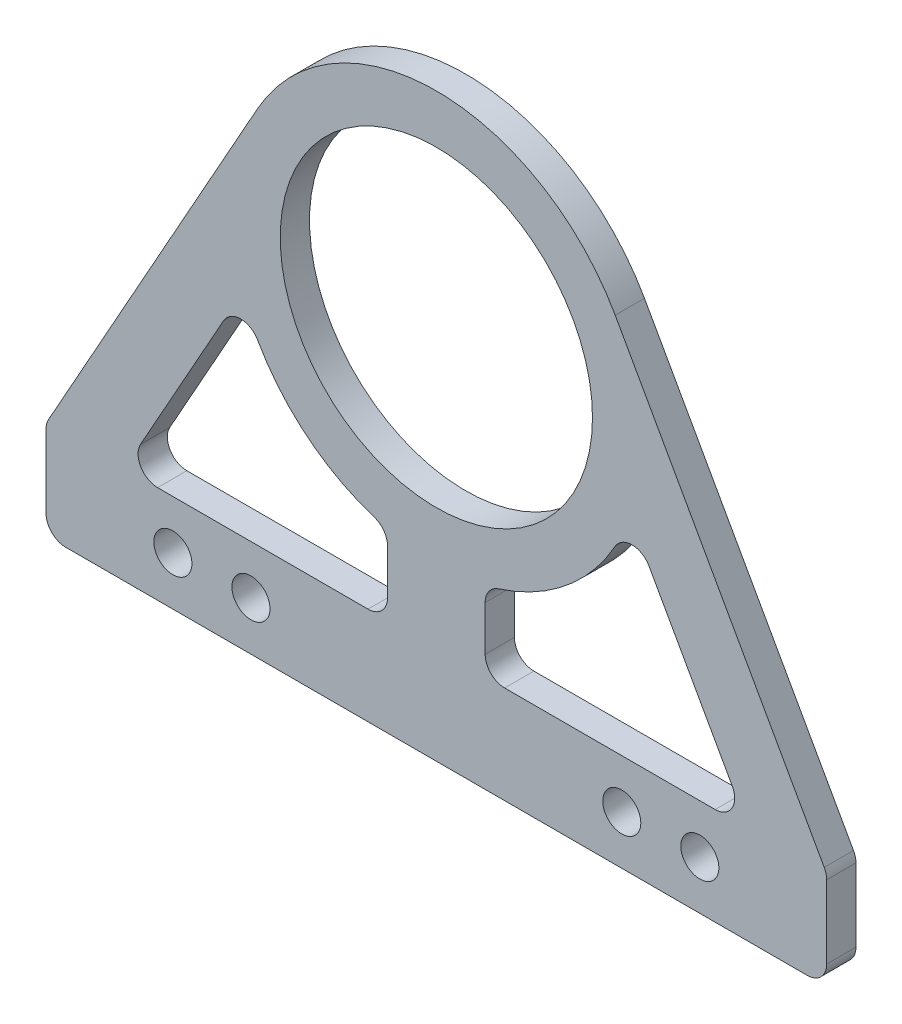
SolidWorks part; units mm, degrees
material "Thornel Mat VMA"
ref_plane "前视基准面" through (0, 0, 0) normal (0, 0, 1) x (1, 0, 0)
ref_plane "上视基准面" through (0, 0, 0) normal (0, 1, 0) x (1, 0, 0)
ref_plane "右视基准面" through (0, 0, 0) normal (1, 0, 0) x (0, 0, -1)
other "Configuration Table"
sketch "草图1" plane through (0, 0, 0) normal (0, 0, 1) x (1, 0, 0)
  line L0 (-40, -28.5) -> (-40, -38.5)
  line L1 (40, -28.5) -> (18.3284, 10.2504)
  line L2 (-18.3284, 10.2504) -> (-40, -28.5)
  line L3 (-40, -38.5) -> (40, -38.5)
  line L4 (40, -38.5) -> (40, -28.5)
  line L5 (-40, -33.5) -> (40, -33.5) construction
  circle A0 centre (0, 0) radius 16
  arc A1 (18.3284, 10.2504) -> (-18.3284, 10.2504) centre (0, 0) ccw
  circle A2 centre (27, -33.5) radius 1.95
  circle A3 centre (19, -33.5) radius 1.95
  circle A4 centre (-27, -33.5) radius 1.95
  circle A5 centre (-19, -33.5) radius 1.95
  dimension "D1" = 32
  dimension "D2" = 5
  dimension "D6" = 3.9
  dimension "D7" = 8
  dimension "D8" = 13
  dimension "D9" = 8
  dimension "D10" = 13
  dimension "D3" = 10
  dimension "D4" = 80
  dimension "D5" = 38.5
extrude "凸台-拉伸1" add sketch "草图1" along normal blind 3
sketch "草图2" plane through (0, 0, 3) normal (0, 0, 1) x (1, 0, 0)
  line L0 (-31.9797, -28.5) -> (-5, -28.5)
  line L1 (-5, -20.3961) -> (-5, -28.5)
  line L2 (0, 0) -> (0, -28.5) construction
  line L3 (-19.8591, -6.8276) -> (-31.9797, -28.5)
  line L4 (-18.3284, 10.2504) -> (-40, -28.5) construction
  line L5 (19.8591, -6.8276) -> (31.9797, -28.5)
  line L6 (5, -20.3961) -> (5, -28.5)
  line L7 (31.9797, -28.5) -> (5, -28.5)
  arc A0 (-19.8591, -6.8276) -> (-5, -20.3961) centre (0, 0) ccw
  arc A1 (18.3284, 10.2504) -> (-18.3284, 10.2504) centre (0, 0) ccw construction
  arc A2 (19.8591, -6.8276) -> (5, -20.3961) centre (0, 0) cw
  dimension "D1" = 5
  dimension "D2" = 7
extrude "切除-拉伸1" cut sketch "草图2" against normal through all
fillet "圆角1" radius 2 12 edges at (40, -28.5, 1.5) (40, -38.5, 1.5) (-40, -38.5, 1.5) (-40, -28.5, 1.5) (-5, -20.3961, 1.5) (-5, -28.5, 1.5) (31.9797, -28.5, 1.5) (5, -28.5, 1.5) (5, -20.3961, 1.5) (19.8591, -6.8276, 1.5) (-19.8591, -6.8276, 1.5) (-31.9797, -28.5, 1.5)
